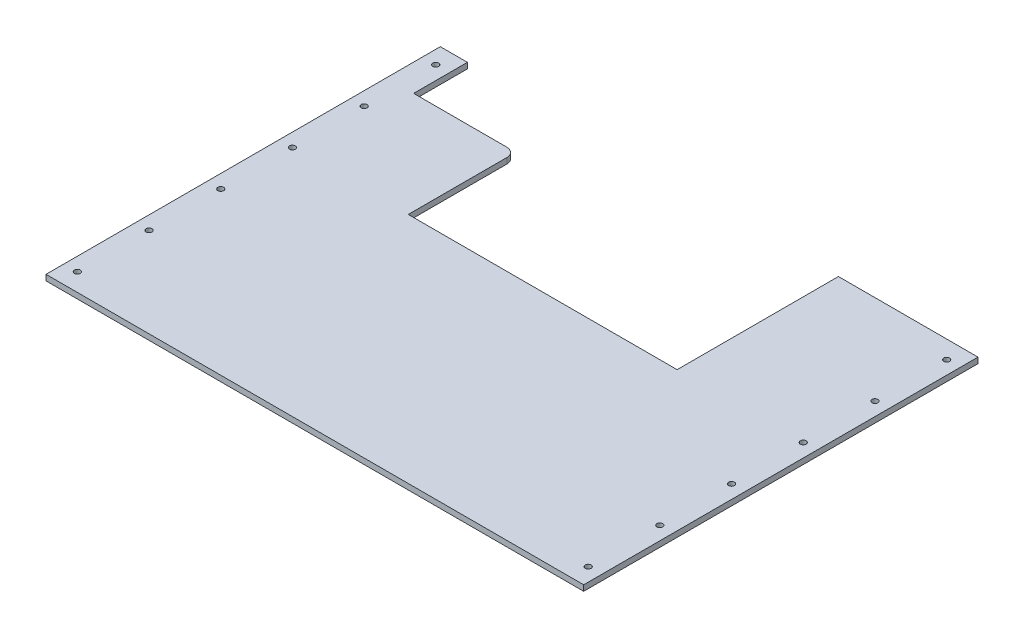
SolidWorks part; units mm, degrees
material "PC High Viscosity"
ref_plane "Front" through (0, 0, 0) normal (0, 0, 1) x (1, 0, 0)
ref_plane "Top" through (0, 0, 0) normal (0, 1, 0) x (1, 0, 0)
ref_plane "Right" through (0, 0, 0) normal (1, 0, 0) x (0, 0, -1)
sketch "Sketch1" plane through (0, 0, 0) normal (0, 1, 0) x (1, 0, 0)
  line L0 (72.1275, 91.8553) -> (72.1275, 1.8553)
  line L1 (-150, 91.8553) -> (-134.8725, 91.8553)
  line L2 (-150, 91.8553) -> (-150, -128.1447)
  line L3 (-150, -128.1447) -> (150, -128.1447)
  line L4 (150, 91.8553) -> (150, -128.1447)
  line L5 (72.1275, 1.8553) -> (-77.8725, 1.8553)
  line L6 (-77.8725, 1.8553) -> (-77.8725, 61.8553)
  line L7 (-77.8725, 61.8553) -> (-134.8725, 61.8553)
  line L8 (-134.8725, 61.8553) -> (-134.8725, 91.8553)
  line L10 (72.1275, 91.8553) -> (150, 91.8553)
  dimension "D1" = 300
  dimension "D2" = 220
  dimension "D3" = 150
  dimension "D4" = 90
  dimension "D5" = 60
  dimension "D6" = 57
extrude "Boss-Extrude1" add sketch "Sketch1" along normal blind 3.18
sketch "Sketch2" plane through (0, 3.18, 0) normal (0, 1, 0) x (1, 0, 0)
  line L0 (-150, 91.8553) -> (-150, -128.1447) construction
  line L1 (-134.8725, 91.8553) -> (-150, 91.8553) construction
  line L3 (150, -128.1447) -> (150, 91.8553) construction
  circle A0 centre (-142.5, 81.8553) radius 1.65
  circle A1 centre (-142.5, 41.8553) radius 1.65
  circle A2 centre (-142.5, 1.8553) radius 1.65
  circle A3 centre (-142.5, -38.1447) radius 1.65
  circle A4 centre (-142.5, -78.1447) radius 1.65
  circle A5 centre (-142.5, -118.1447) radius 1.65
  circle A6 centre (142.5, 81.8553) radius 1.65
  circle A7 centre (142.5, 41.8553) radius 1.65
  circle A8 centre (142.5, 1.8553) radius 1.65
  circle A9 centre (142.5, -38.1447) radius 1.65
  circle A10 centre (142.5, -78.1447) radius 1.65
  circle A11 centre (142.5, -118.1447) radius 1.65
  dimension "D1" = 3.3
  dimension "D4" = 6
  dimension "D8" = 6
  dimension "D2" = 7.5
  dimension "D3" = 10
  dimension "D6" = 10
  dimension "D7" = 7.5
extrude "Cut-Extrude1" cut sketch "Sketch2" against normal blind 10
fillet "Fillet1" radius 5 1 edges at (-77.8725, 1.59, -61.8553)
